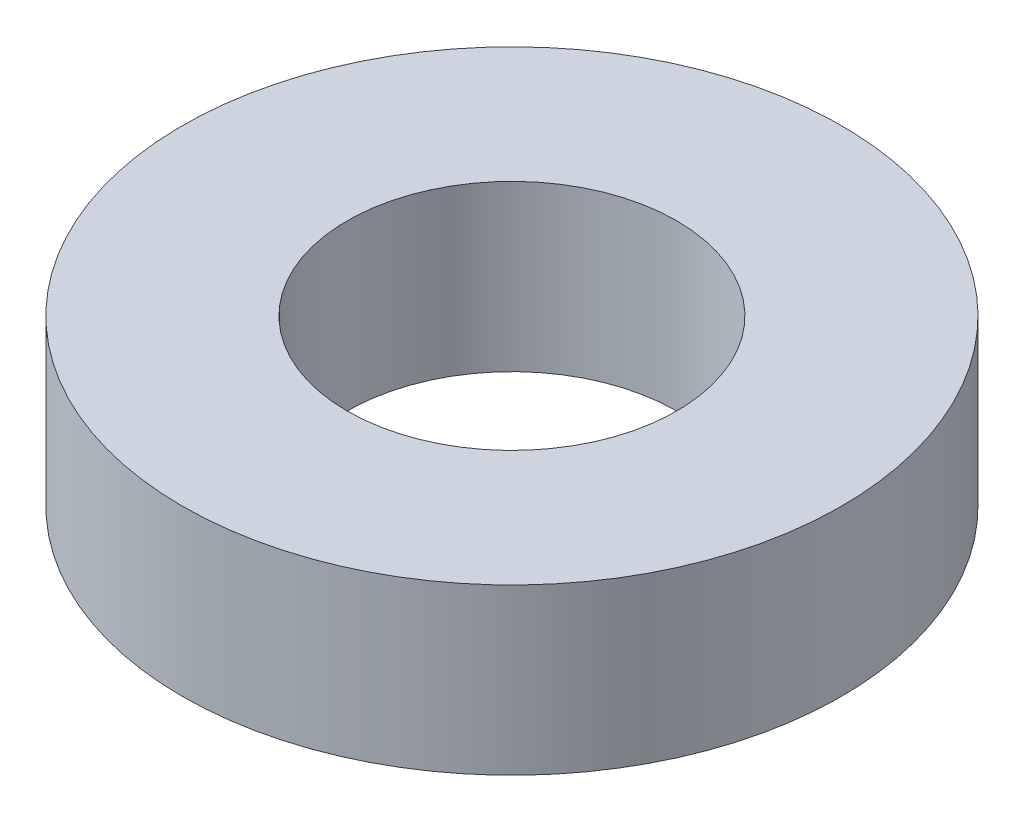
SolidWorks part; units mm, degrees
ref_plane "Front Plane" through (0, 0, 0) normal (0, 0, 1) x (1, 0, 0)
ref_plane "Top Plane" through (0, 0, 0) normal (0, 1, 0) x (1, 0, 0)
ref_plane "Right Plane" through (0, 0, 0) normal (1, 0, 0) x (0, 0, -1)
sketch "Sketch1" plane through (0, 0, 0) normal (0, 1, 0) x (1, 0, 0)
  circle A0 centre (0, 0) radius 6
extrude "Boss-Extrude1" add sketch "Sketch1" along normal blind 3
sketch "Sketch2" plane through (0, 3, 0) normal (0, 1, 0) x (1, 0, 0)
  circle A0 centre (0, 0) radius 3
extrude "Cut-Extrude1" cut sketch "Sketch2" against normal through all
